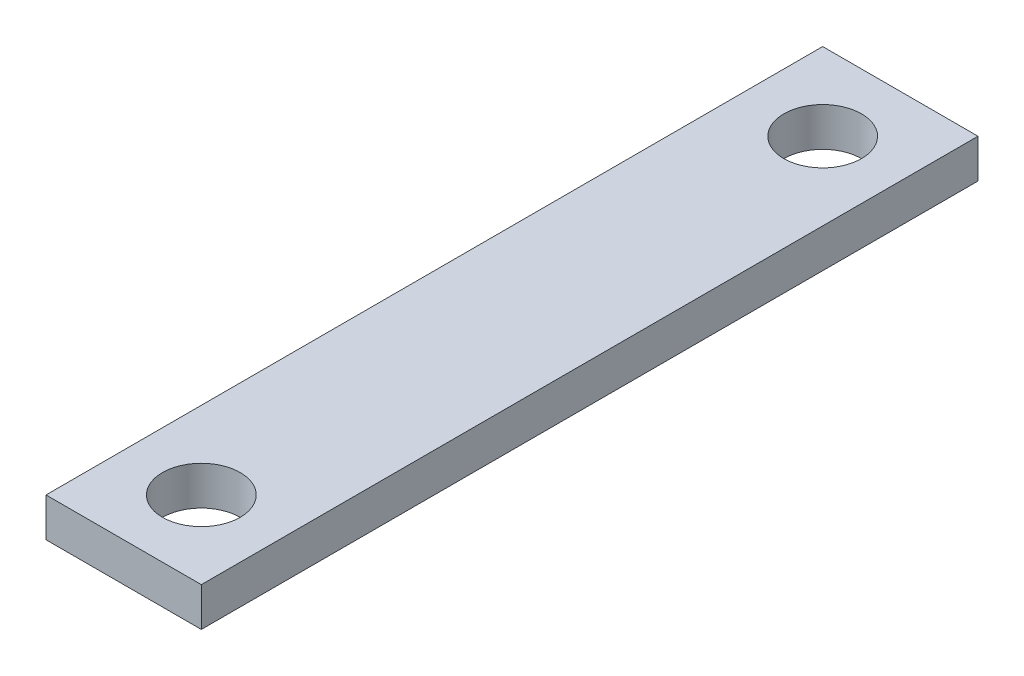
SolidWorks part; units mm, degrees
ref_plane "Front Plane" through (0, 0, 0) normal (0, 0, 1) x (1, 0, 0)
ref_plane "Top Plane" through (0, 0, 0) normal (0, 1, 0) x (1, 0, 0)
ref_plane "Right Plane" through (0, 0, 0) normal (1, 0, 0) x (0, 0, -1)
sketch "Sketch1" plane through (0, 0, 0) normal (0, 1, 0) x (1, 0, 0)
  line L0 (6.35, 63.5) -> (6.35, 57.15) construction
  line L1 (0, 0) -> (12.7, 0)
  line L2 (0, 0) -> (0, 63.5)
  line L3 (0, 63.5) -> (12.7, 63.5)
  line L4 (12.7, 0) -> (12.7, 63.5)
  line L5 (6.35, 57.15) -> (6.35, 6.35) construction
  line L6 (6.35, 6.35) -> (6.35, 0) construction
  circle A0 centre (6.35, 57.15) radius 3.175
  circle A1 centre (6.35, 6.35) radius 3.175
  dimension "D1" = 6.35
  dimension "D2" = 6.35
  dimension "D3" = 63.5
  dimension "D4" = 12.7
extrude "Boss-Extrude1" add sketch "Sketch1" along normal blind 3.175
